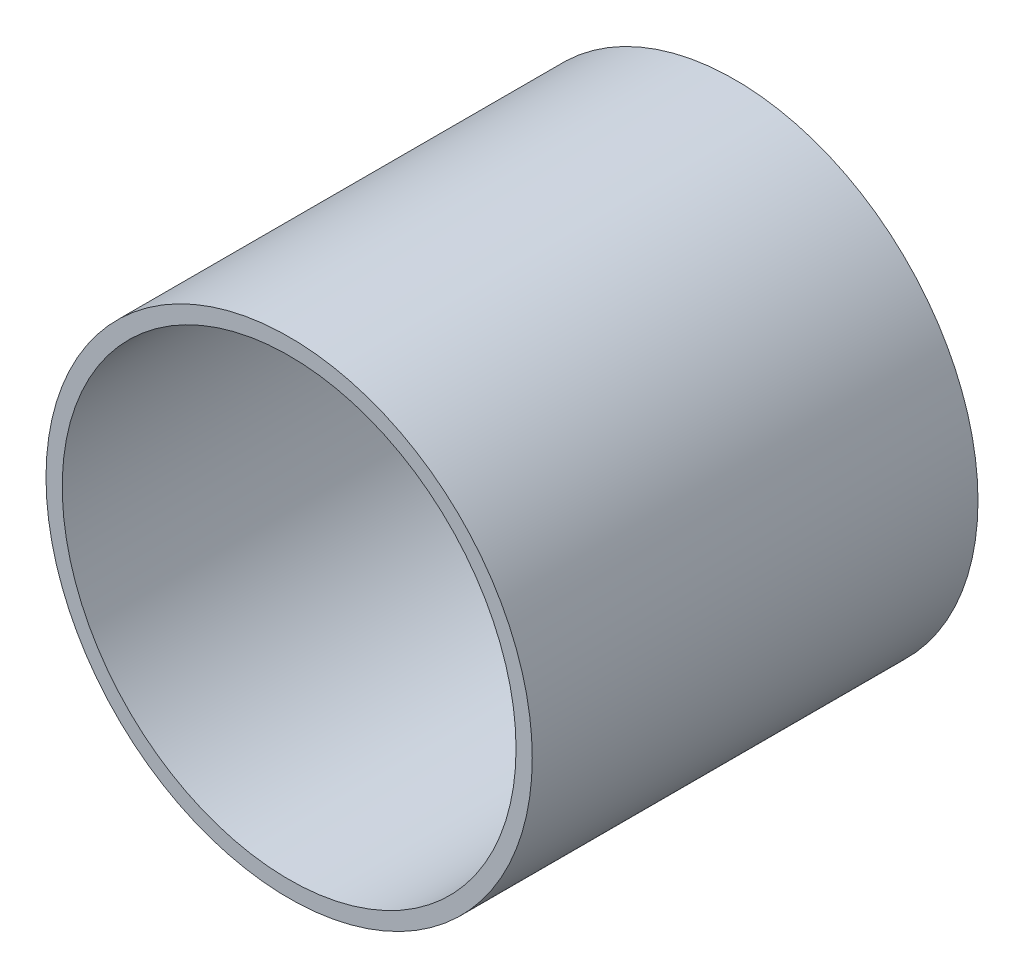
SolidWorks part; units mm, degrees
material "1.6566 (17NiCrMo6-4)"
ref_plane "Plan de face" through (0, 0, 0) normal (0, 0, 1) x (1, 0, 0)
ref_plane "Plan de dessus" through (0, 0, 0) normal (0, 1, 0) x (1, 0, 0)
ref_plane "Plan de droite" through (0, 0, 0) normal (1, 0, 0) x (0, 0, -1)
sketch "Esquisse1" plane through (0, 0, 0) normal (0, 0, 1) x (1, 0, 0)
  circle A0 centre (0, 0) radius 3
  circle A1 centre (0, 0) radius 2.8
  dimension "D1" = 6
  dimension "D2" = 0.2
extrude "Bushing" add sketch "Esquisse1" along normal blind 5.5
